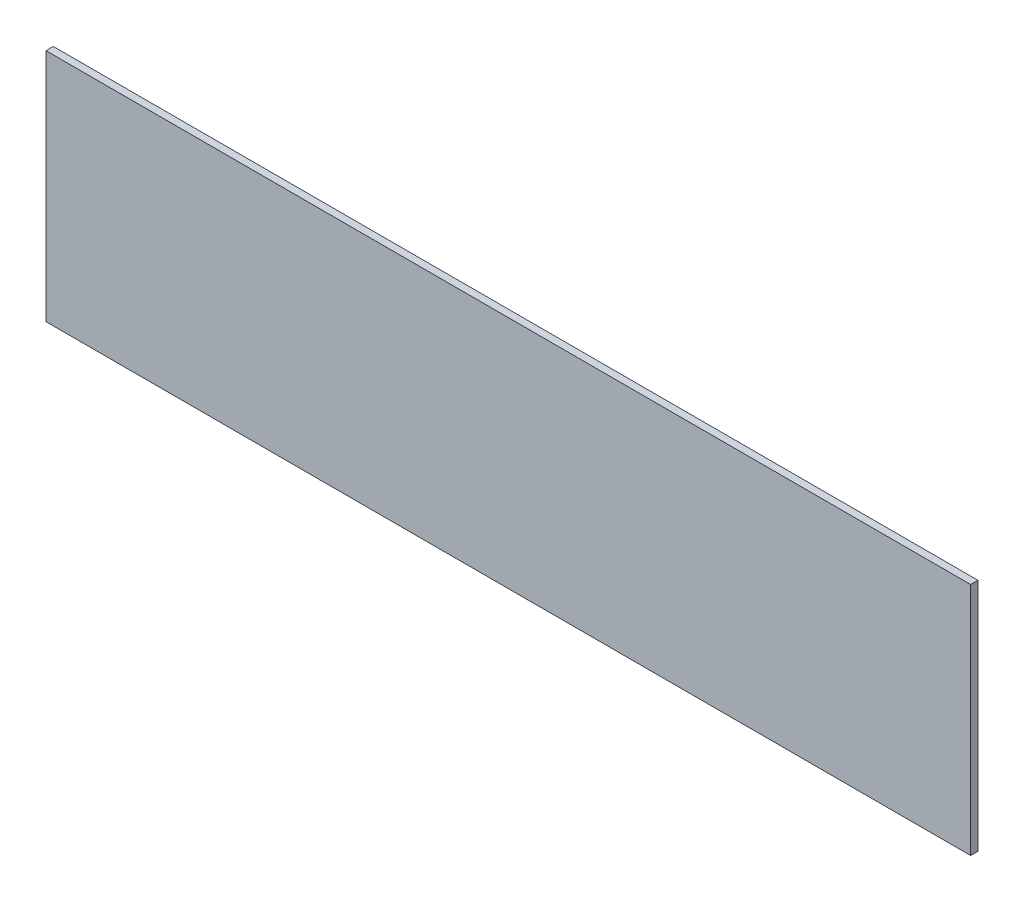
SolidWorks part; units mm, degrees
material "ABS"
ref_plane "X-Y Datum" through (0, 0, 0) normal (0, 0, 1) x (1, 0, 0)
ref_plane "X-Z Datum" through (0, 0, 0) normal (0, 1, 0) x (1, 0, 0)
ref_plane "Y-Z Datum" through (0, 0, 0) normal (1, 0, 0) x (0, 0, -1)
sketch "Sketch1" plane through (0, 0, 0) normal (0, 0, 1) x (1, 0, 0)
  line L1 (-149.85, 38.0375) -> (149.85, 38.0375)
  line L2 (-149.85, 38.0375) -> (-149.85, -38.0375)
  line L3 (-149.85, -38.0375) -> (149.85, -38.0375)
  line L4 (149.85, 38.0375) -> (149.85, -38.0375)
  line L5 (-149.85, 38.0375) -> (149.85, -38.0375) construction
  line L6 (-149.85, -38.0375) -> (149.85, 38.0375) construction
  point P0 (0, 0)
  dimension "D1" = 76.075
  dimension "D2" = 299.7
extrude "Boss-Extrude1" add sketch "Sketch1" along normal blind 2.3813
